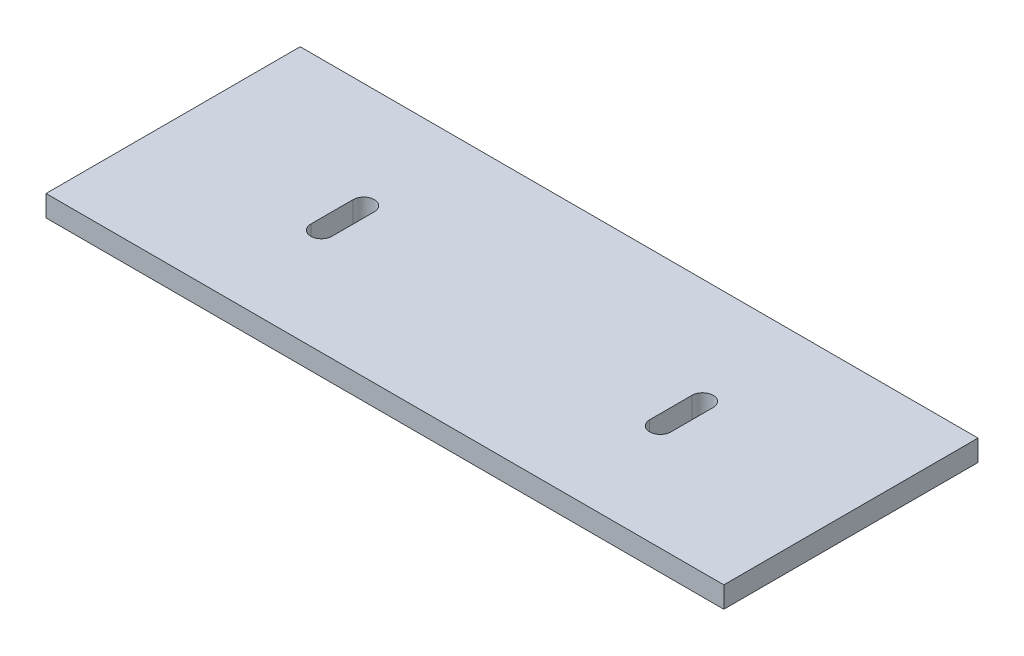
SolidWorks part; units mm, degrees
material "ASTM A36 Steel"
ref_plane "Front Plane" through (0, 0, 0) normal (0, 0, 1) x (1, 0, 0)
ref_plane "Top Plane" through (0, 0, 0) normal (0, 1, 0) x (1, 0, 0)
ref_plane "Right Plane" through (0, 0, 0) normal (1, 0, 0) x (0, 0, -1)
sketch "Sketch1" plane through (0, 0, 0) normal (0, 1, 0) x (1, 0, 0)
  line L0 (0, -38.1) -> (0, 38.1) construction
  line L1 (-101.6, -38.1) -> (101.6, -38.1)
  line L2 (-101.6, -38.1) -> (-101.6, 38.1)
  line L3 (-101.6, 38.1) -> (101.6, 38.1)
  line L4 (101.6, -38.1) -> (101.6, 38.1)
  line L5 (-101.6, -38.1) -> (101.6, 38.1) construction
  line L6 (-101.6, 38.1) -> (101.6, -38.1) construction
  line L7 (-101.6, 0) -> (101.6, 0) construction
  line L8 (-50.8, -6.35) -> (-50.8, 6.35) construction
  line L9 (-53.975, -6.35) -> (-53.975, 6.35)
  line L10 (-47.625, -6.35) -> (-47.625, 6.35)
  line L11 (50.8, -6.35) -> (50.8, 6.35) construction
  line L12 (53.975, -6.35) -> (53.975, 6.35)
  line L13 (47.625, -6.35) -> (47.625, 6.35)
  arc A0 (-53.975, -6.35) -> (-47.625, -6.35) centre (-50.8, -6.35) ccw
  arc A1 (-47.625, 6.35) -> (-53.975, 6.35) centre (-50.8, 6.35) ccw
  arc A2 (53.975, -6.35) -> (47.625, -6.35) centre (50.8, -6.35) cw
  arc A3 (47.625, 6.35) -> (53.975, 6.35) centre (50.8, 6.35) cw
  point P0 (0, 0)
  point P10 (-50.8, 0)
  point P18 (50.8, 0)
  dimension "D3" = 12.7
  dimension "D4" = 3.175
  dimension "D5" = 50.8
  dimension "D1" = 203.2
  dimension "D2" = 76.2
extrude "Boss-Extrude1" add sketch "Sketch1" along normal blind 6.35
